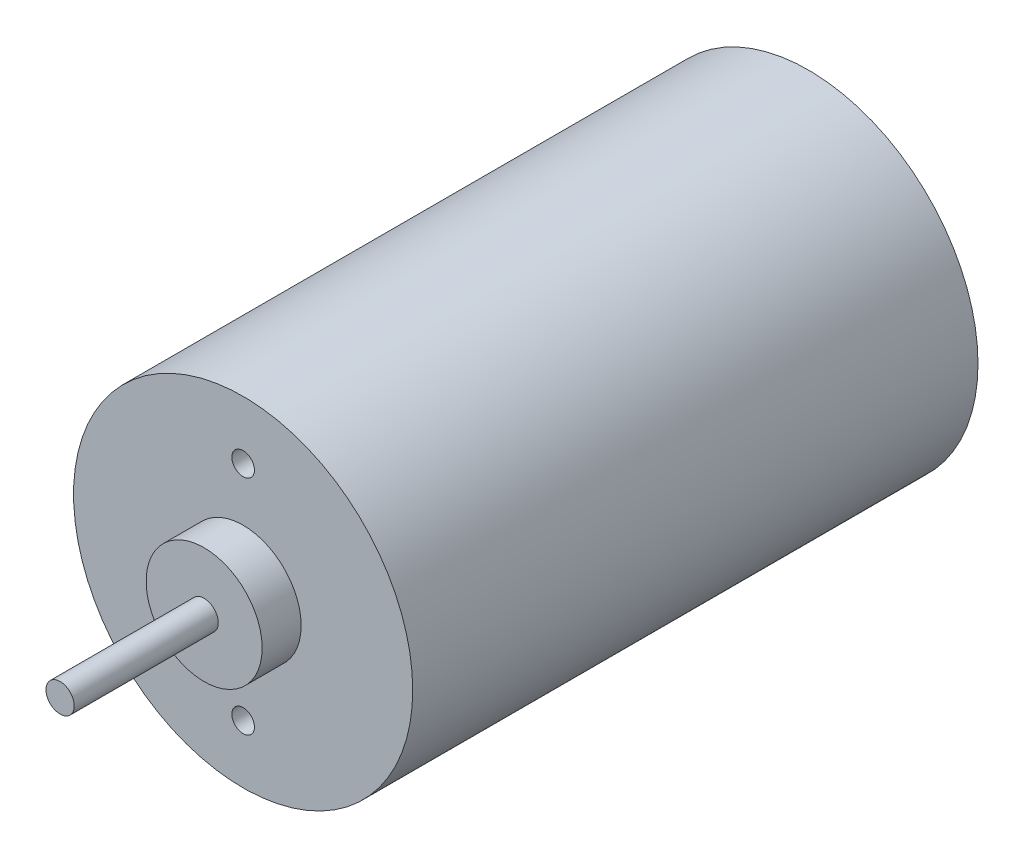
SolidWorks part; units mm, degrees
ref_plane "Front Plane" through (0, 0, 0) normal (0, 0, 1) x (1, 0, 0)
ref_plane "Top Plane" through (0, 0, 0) normal (0, 1, 0) x (1, 0, 0)
ref_plane "Right Plane" through (0, 0, 0) normal (1, 0, 0) x (0, 0, -1)
sketch "Sketch1" plane through (0, 0, 0) normal (0, 0, 1) x (1, 0, 0)
  circle A0 centre (0, 0) radius 19.05
  dimension "D1" = 38.1
extrude "Boss-Extrude1" add sketch "Sketch1" along normal blind 63.5
sketch "Sketch2" plane through (0, 0, 63.5) normal (0, 0, 1) x (1, 0, 0)
  circle A0 centre (0, 0) radius 6.5151
  dimension "D1" = 13.0302
extrude "Boss-Extrude2" add sketch "Sketch2" along normal blind 4.3815
sketch "Sketch3" plane through (0, 0, 67.8815) normal (0, 0, 1) x (1, 0, 0)
  circle A0 centre (0, 0) radius 1.5875
  dimension "D1" = 3.175
extrude "Boss-Extrude3" add sketch "Sketch3" along normal blind 16.1798
sketch "Sketch4" plane through (0, 0, 63.5) normal (0, 0, 1) x (1, 0, 0)
  circle A0 centre (0, 0) radius 12.5 construction
  circle A1 centre (0, 12.5) radius 1.27
  circle A2 centre (0, -12.5) radius 1.27
  dimension "D1" = 25
  dimension "D2" = 2.54
  dimension "D3" = 2.54
extrude "Cut-Extrude1" cut sketch "Sketch4" against normal blind 6.35
